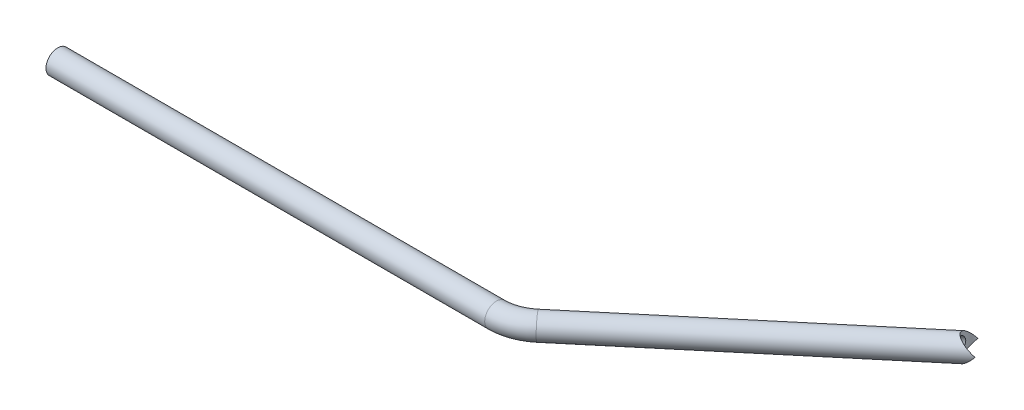
SolidWorks part; units mm, degrees
ref_plane "Front Plane" through (0, 0, 0) normal (0, 0, 1) x (1, 0, 0)
ref_plane "Top Plane" through (0, 0, 0) normal (0, 1, 0) x (1, 0, 0)
ref_plane "Right Plane" through (0, 0, 0) normal (1, 0, 0) x (0, 0, -1)
sketch "Sketch2" plane through (0, 0, 0) normal (0, 1, 0) x (1, 0, 0)
  line L0 (0, 0) -> (1869.0525, 0)
  line L1 (1997.61, 46.7911) -> (3014.4248, 900)
  arc A0 (1869.0525, 0) -> (1997.61, 46.7911) centre (1869.0525, 200) ccw
  dimension "D4" = 200
  dimension "D1" = 140
  dimension "D2" = 900
  dimension "D3" = 3014.4248
sketch "Sketch3" plane through (0, 0, 0) normal (1, 0, 0) x (0, 0, -1)
  circle A0 centre (0, 0) radius 50
  circle A1 centre (0, 0) radius 35
  dimension "D1" = 100
  dimension "D2" = 15
sweep "Sweep1" add profiles "Sketch3" path "Sketch2"
sketch "Sketch4" plane through (0, 0, 0) normal (0, 1, 0) x (1, 0, 0)
  line L0 (3046.5642, 861.6978) -> (2982.2854, 938.3022) construction
  circle A0 centre (3014.4248, 900) radius 50
  dimension "D1" = 100
extrude "Cut-Extrude1" cut sketch "Sketch4" against normal through all both and the other way through all
equation "\"hatchHoleDiameter\"= 600mm"
equation "\"hullThickness\"= 120mm"
equation "\"gasketHullInterconnectWidth\"= 100mm"
equation "\"collarThickness\"= 15"
equation "\"hatchTunnelLength\"=200"
equation "\"oRingDiameter\"=2"
equation "\"boltPatternRadiusInterconnect\"=500"
equation "\"interconnectBoltDiameter\"=30"
equation "\"hatchShaftDiameter\"=20"
equation "\"hatchMinima\"=50"
equation "\"hullDiameter\"=2000"
equation "\"hatchMaxima\"=180"
equation "\"bushingFlatHatch\"=15"
equation "\"hingePivotDiameter\"=20"
equation "\"handleWidth\"=250"
equation "\"handleHeight\"=160"
equation "\"handleThickness\"=25"
equation "\"FrameLength\"= 4300"
equation "\"FrameMidLength\"= 3000"
equation "\"TubeOD\"= 100"
equation "\"FrameBackFlat\"= 800"
equation "\"TubeWall\"=15"
equation "\"TopMemberAngle\"=120"
equation "\"FrameHight\"= 2500"
equation "\"FrameMidMemAngle\"=140"
equation "\"D1@Sketch2\"=\"FrameMidMemAngle\""
equation "\"D2@Sketch2\"=\"hullDiameter\"/2 *.9"
equation "\"D3@Sketch2\"=\"FrameLength\"-\"hullDiameter\"*sin( 180-\"FrameMidMemAngle\")"
equation "\"D1@Sketch3\"=\"TubeOD\""
equation "\"D1@Sketch4\"=\"TubeOD\""
